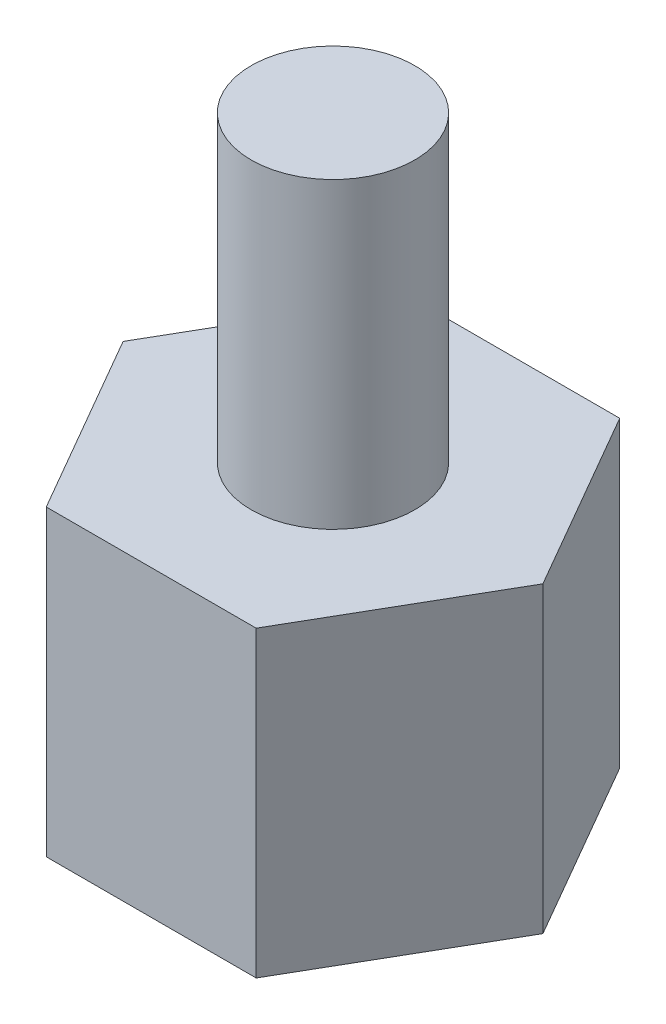
SolidWorks part; units mm, degrees
ref_plane "정면도" through (0, 0, 0) normal (0, 0, 1) x (1, 0, 0)
ref_plane "평면도" through (0, 0, 0) normal (0, 1, 0) x (1, 0, 0)
ref_plane "우측면도" through (0, 0, 0) normal (1, 0, 0) x (0, 0, -1)
sketch "스케치1" plane through (0, 0, 0) normal (0, 1, 0) x (1, 0, 0)
  line L1 (3.4641, 0) -> (1.7321, 3)
  line L2 (1.7321, 3) -> (-1.7321, 3)
  line L3 (-1.7321, 3) -> (-3.4641, 0)
  line L4 (-3.4641, 0) -> (-1.7321, -3)
  line L5 (-1.7321, -3) -> (1.7321, -3)
  line L6 (1.7321, -3) -> (3.4641, 0)
  circle A0 centre (0, 0) radius 3 construction
  dimension "D1" = 6
extrude "보스-돌출1" add sketch "스케치1" along normal blind 5
sketch "스케치2" plane through (0, 5, 0) normal (0, 1, 0) x (1, 0, 0)
  circle A0 centre (0, 0) radius 1.35
  dimension "D1" = 2.7
extrude "보스-돌출2" add sketch "스케치2" along normal blind 5
sketch "스케치3" plane through (0, 0, 0) normal (0, -1, 0) x (1, 0, 0)
  circle A0 centre (0, 0) radius 1.35
  dimension "D1" = 2.7
extrude "컷-돌출1" cut sketch "스케치3" against normal blind 4
